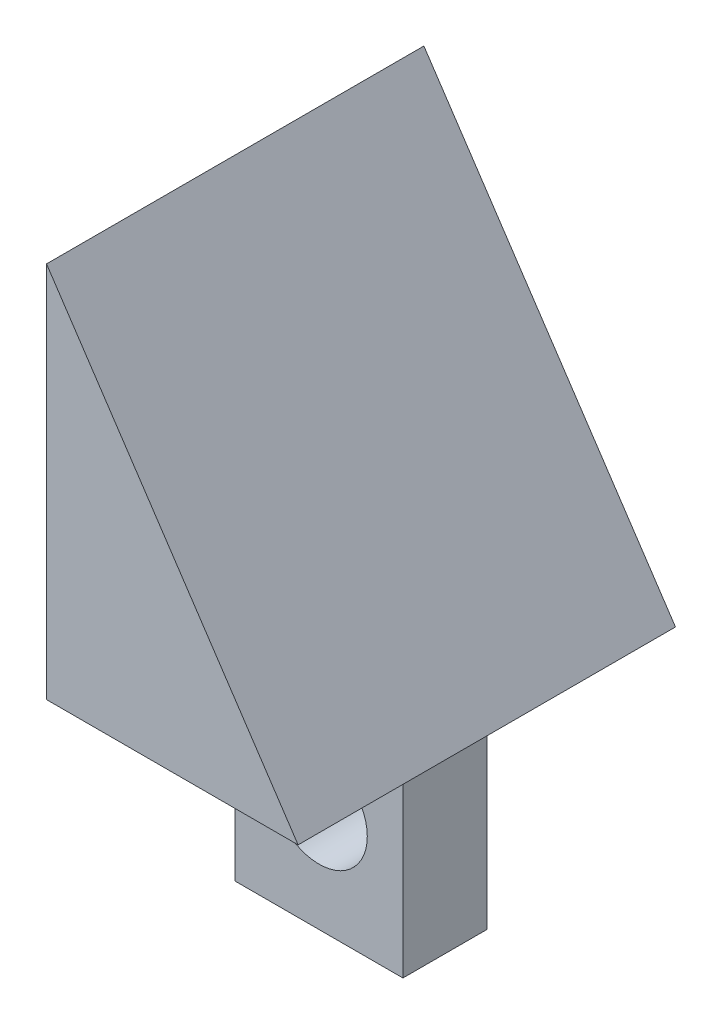
SolidWorks part; units mm, degrees
ref_plane "Front Plane" through (0, 0, 0) normal (0, 0, 1) x (1, 0, 0)
ref_plane "Top Plane" through (0, 0, 0) normal (0, 1, 0) x (1, 0, 0)
ref_plane "Right Plane" through (0, 0, 0) normal (1, 0, 0) x (0, 0, -1)
sketch "Sketch1" plane through (0, 0, 0) normal (0, 0, 1) x (1, 0, 0)
  line L0 (0, 0) -> (0, 18)
  line L1 (0, 18) -> (12, 0)
  line L2 (12, 0) -> (0, 0)
  dimension "D1" = 18
  dimension "D2" = 12
extrude "Boss-Extrude1" add sketch "Sketch1" along normal blind 18
ref_plane "Plane1" through (0, 0, 9) normal (0, 0, 1) x (1, 0, 0)
sketch "Sketch2" plane through (0, 0, 9) normal (0, 0, 1) x (1, 0, 0)
  line L0 (0, 0) -> (12, 0) construction
  line L1 (2, 0) -> (10, 0)
  line L2 (2, 0) -> (2, -10)
  line L3 (2, -10) -> (10, -10)
  line L4 (10, 0) -> (10, -10)
  line L5 (6, -10) -> (6, 0) construction
  line L6 (10, -5) -> (2, -5) construction
  circle A0 centre (6, -5) radius 2.3
  dimension "D1" = 4.6
  dimension "D2" = 8
  dimension "D3" = 10
  dimension "D4" = 2
extrude "Boss-Extrude2" add sketch "Sketch2" against normal blind 2 and the other way blind 2
